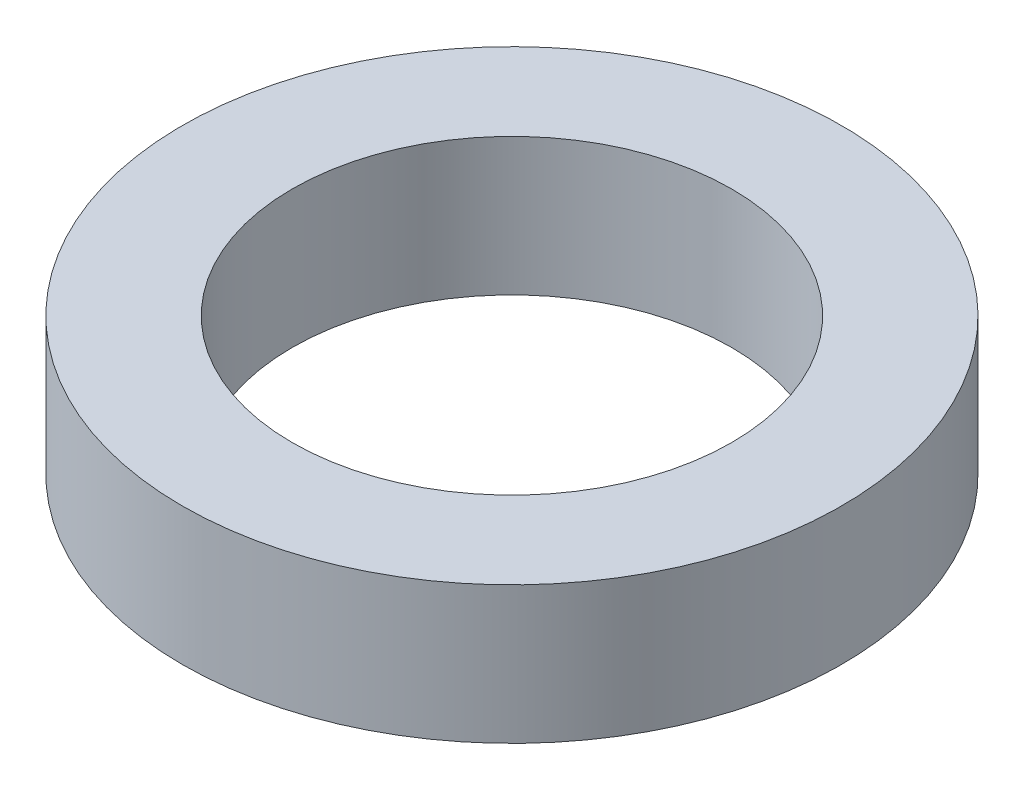
SolidWorks part; units mm, degrees
ref_plane "Front Plane" through (0, 0, 0) normal (0, 0, 1) x (1, 0, 0)
ref_plane "Top Plane" through (0, 0, 0) normal (0, 1, 0) x (1, 0, 0)
ref_plane "Right Plane" through (0, 0, 0) normal (1, 0, 0) x (0, 0, -1)
sketch "Sketch1" plane through (0, 0, 0) normal (0, 1, 0) x (1, 0, 0)
  circle A0 centre (0, 0) radius 9.525
  circle A1 centre (0, 0) radius 6.35
  dimension "D1" = 19.05
  dimension "D2" = 12.7
extrude "Boss-Extrude1" add sketch "Sketch1" along normal blind 3.9688
